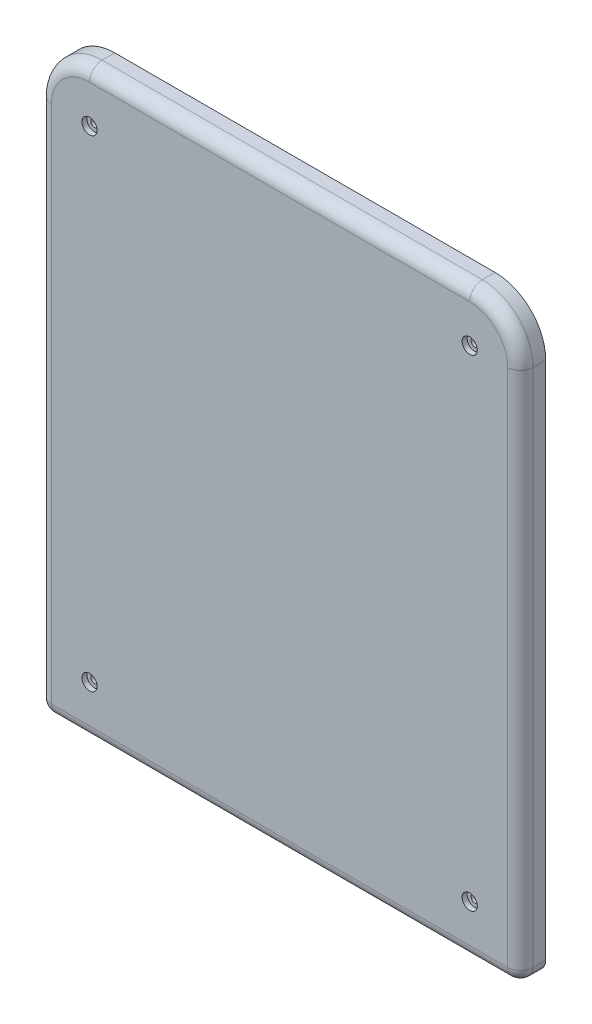
SolidWorks part; units mm, degrees
ref_plane "Front Plane" through (0, 0, 0) normal (0, 0, 1) x (1, 0, 0)
ref_plane "Top Plane" through (0, 0, 0) normal (0, 1, 0) x (1, 0, 0)
ref_plane "Right Plane" through (0, 0, 0) normal (1, 0, 0) x (0, 0, -1)
sketch "Sketch1" plane through (0, 0, 0) normal (0, 0, 1) x (1, 0, 0)
  line L0 (20, 35.7152) -> (170, 35.7152)
  line L1 (190, 15.7152) -> (190, -189.2848)
  line L2 (5, -194.2848) -> (185, -194.2848)
  line L3 (0, 15.7152) -> (0, -189.2848)
  arc A0 (190, -189.2848) -> (185, -194.2848) centre (185, -189.2848) cw
  arc A1 (170, 35.7152) -> (190, 15.7152) centre (170, 15.7152) cw
  arc A3 (0, -189.2848) -> (5, -194.2848) centre (5, -189.2848) ccw
  arc A4 (20, 35.7152) -> (0, 15.7152) centre (20, 15.7152) ccw
extrude "Boss-Extrude1" add sketch "Sketch1" along normal blind 10
fillet "Fillet1" radius 5 8 edges at (95, 35.7152, 10) (184.1421, 29.8573, 10) (190, -86.7848, 10) (188.5355, -192.8204, 10) (95, -194.2848, 10) (1.4645, -192.8204, 10) (0, -86.7848, 10) (5.8579, 29.8573, 10)
sketch "Sketch2" plane through (0, 0, 10) normal (0, 0, 1) x (1, 0, 0)
  line L0 (5, -189.2848) -> (185, -189.2848) construction
  line L1 (20, 15.7152) -> (170, 15.7152) construction
  line L2 (20, 15.7152) -> (20, -174.2848) construction
  line L3 (20, -174.2848) -> (170, -174.2848) construction
  line L4 (170, 15.7152) -> (170, -174.2848) construction
  line L5 (170, 30.7152) -> (20, 30.7152) construction
  line L6 (5, 15.7152) -> (5, -189.2848) construction
  line L7 (185, -189.2848) -> (185, 15.7152) construction
  circle A0 centre (20, -174.2848) radius 1.5
  circle A1 centre (170, -174.2848) radius 1.5
  circle A2 centre (170, 15.7152) radius 1.5
  circle A3 centre (20, 15.7152) radius 1.5
  dimension "D1" = 15
  dimension "D2" = 15
  dimension "D3" = 15
  dimension "D4" = 15
extrude "Cut-Extrude1" cut sketch "Sketch2" against normal up to next
sketch "Sketch3" plane through (0, 0, 10) normal (0, 0, 1) x (1, 0, 0)
  circle A0 centre (20, 15.7152) radius 3
  circle A1 centre (170, 15.7152) radius 3
  circle A2 centre (170, -174.2848) radius 3
  circle A3 centre (20, -174.2848) radius 3
extrude "Cut-Extrude2" cut sketch "Sketch3" against normal blind 2
